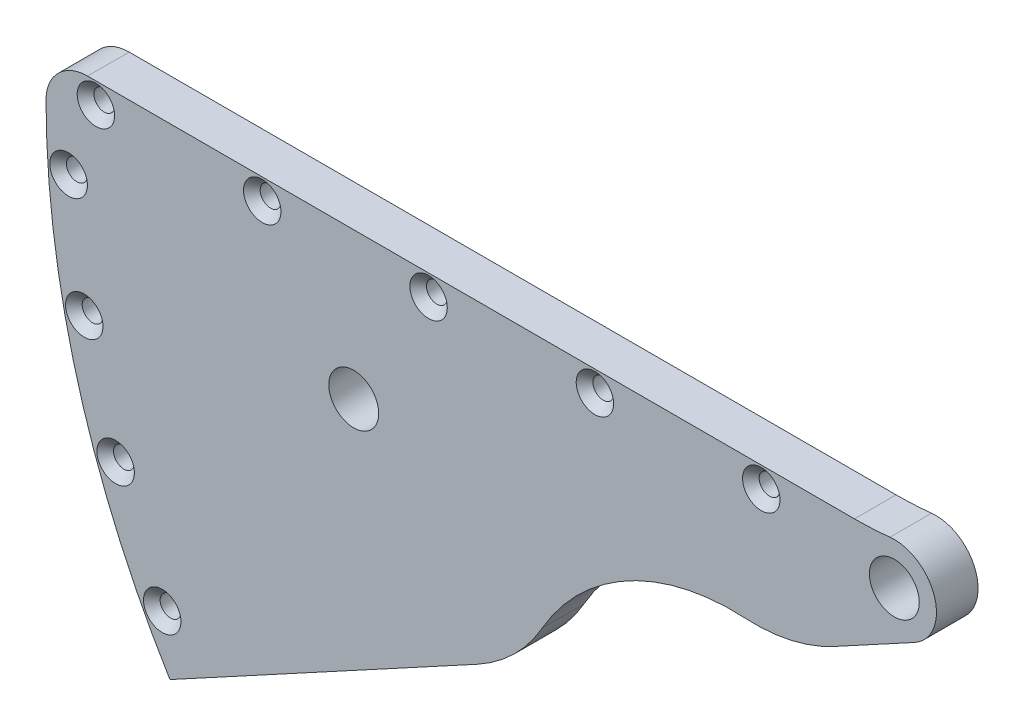
SolidWorks part; units mm, degrees
ref_plane "Front Plane" through (0, 0, 0) normal (0, 0, 1) x (1, 0, 0)
ref_plane "Top Plane" through (0, 0, 0) normal (0, 1, 0) x (1, 0, 0)
ref_plane "Right Plane" through (0, 0, 0) normal (1, 0, 0) x (0, 0, -1)
sketch "Sketch1" plane through (0, 0, 0) normal (0, 0, 1) x (1, 0, 0)
  line L3 (66.8565, -2.7366) -> (-123.9997, -2.7366)
  line L4 (55.4849, -31.7823) -> (74.8359, -21.2714)
  line L5 (-104.2053, -118.5215) -> (-30.3443, -78.4023)
  line L7 (55.4849, -31.7823) -> (74.8359, -21.2714)
  line L8 (-104.2053, -118.5215) -> (-30.3443, -78.4023)
  line L19 (66.8565, -2.7366) -> (-123.9997, -2.7366)
  circle A0 centre (-122, -7.7366) radius 2.5 construction
  circle A1 centre (-82, -7.7366) radius 2.5 construction
  circle A2 centre (-42, -7.7366) radius 2.5 construction
  circle A3 centre (-2, -7.7366) radius 2.5 construction
  circle A4 centre (38, -7.7366) radius 2.5 construction
  circle A5 centre (-122, -7.7366) radius 2.5
  arc A6 (-133.9996, -12.7556) -> (-104.2053, -118.5215) centre (70, -12.3683) ccw
  arc A8 (74.8359, -21.2714) -> (66.8565, -2.7366) centre (70, -12.3683) ccw
  arc A9 (34.1104, -36.5677) -> (55.4849, -31.7823) centre (36.3927, 3.3672) ccw
  arc A10 (34.1104, -36.5677) -> (-14.6947, -63.0772) centre (31.102, -89.2099) ccw
  arc A11 (-30.3443, -78.4023) -> (-14.6947, -63.0772) centre (-49.4365, -43.2528) ccw
  arc A14 (74.8359, -21.2714) -> (66.8565, -2.7366) centre (70, -12.3683) ccw
  arc A15 (34.1104, -36.5677) -> (55.4849, -31.7823) centre (36.3927, 3.3672) ccw
  arc A16 (34.1104, -36.5677) -> (-14.6947, -63.0772) centre (31.102, -89.2099) ccw
  arc A17 (-30.3443, -78.4023) -> (-14.6947, -63.0772) centre (-49.4365, -43.2528) ccw
  circle A18 centre (-82, -7.7366) radius 2.5
  circle A19 centre (-42, -7.7366) radius 2.5
  circle A20 centre (-2, -7.7366) radius 2.5
  circle A21 centre (38, -7.7366) radius 2.5
  arc A53 (-133.9996, -12.7556) -> (-104.2053, -118.5215) centre (70, -12.3683) ccw
  arc A54 (-123.9997, -2.7366) -> (-133.9996, -12.7556) centre (-123.9997, -12.7366) ccw
  arc A55 (-123.9997, -2.7366) -> (-133.9996, -12.7556) centre (-123.9997, -12.7366) ccw
  dimension "D1" = 0
extrude "Boss-Extrude1" add sketch "Sketch1" along normal blind 10
chamfer "Chamfer1" distance 2 angle 45 5 edges at (40.5, -7.7366, 10) (0.5, -7.7366, 10) (-39.5, -7.7366, 10) (-79.5, -7.7366, 10) (-119.5, -7.7366, 10)
sketch "Sketch2" plane through (0, 0, 10) normal (0, 0, 1) x (1, 0, 0)
  circle A0 centre (70, -12.3683) radius 6 construction
  circle A1 centre (70, -12.3683) radius 6
extrude "Cut-Extrude1" cut sketch "Sketch2" against normal blind 48
sketch "Sketch3" plane through (0, 0, 10) normal (0, 0, 1) x (1, 0, 0)
  circle A0 centre (-60, -38) radius 6 construction
  circle A1 centre (-60, -38) radius 6
extrude "Cut-Extrude2" cut sketch "Sketch3" against normal blind 14
sketch "Sketch4" plane through (0, 0, 10) normal (0, 0, 1) x (1, 0, 0)
  circle A0 centre (-128.5655, -25.5108) radius 2.5285
  circle A1 centre (-124.804, -53.0179) radius 2.5
  circle A2 centre (-117.2509, -79.7337) radius 2.5
  circle A3 centre (-106.0531, -105.1384) radius 2.5
extrude "Cut-Extrude3" cut sketch "Sketch4" against normal blind 14
chamfer "Chamfer2" distance 2 angle 45 4 edges at (-103.5531, -105.1384, 10) (-114.7509, -79.7337, 10) (-122.304, -53.0179, 10) (-126.037, -25.5108, 10)
fillet "Fillet1" radius 82 1 edges at (66.8565, -2.7366, 5)
